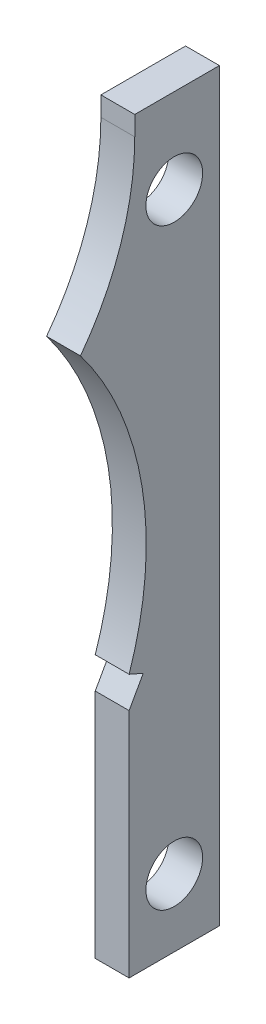
SolidWorks part; units mm, degrees
ref_plane "Front Plane" through (0, 0, 0) normal (0, 0, 1) x (1, 0, 0)
ref_plane "Top Plane" through (0, 0, 0) normal (0, 1, 0) x (1, 0, 0)
ref_plane "Right Plane" through (0, 0, 0) normal (1, 0, 0) x (0, 0, -1)
sketch "Sketch1" plane through (0, 0, 0) normal (1, 0, 0) x (0, 0, -1)
  line L0 (0, 55) -> (0, -55) construction
  line L1 (0, 66) -> (-15, 66)
  line L2 (0, 66) -> (0, -66)
  line L3 (0, -66) -> (-16, -66)
  line L4 (-15, 66) -> (-15, 62.56)
  line L5 (-16, -19.4031) -> (-13.5007, -20.5015)
  line L6 (-16, -24.97) -> (-16, -66)
  line L9 (-13.5007, -20.5015) -> (-16, -24.97)
  arc A1 (-16, -19.4031) -> (-24.621, 33.7655) centre (-70.52, -0.96) ccw
  arc A2 (-24.621, 33.7655) -> (-15, 62.56) centre (-62.9, 62.56) ccw
  point P7 (0, 0)
  dimension "D3" = 115.11
  dimension "D6" = 95.8
  dimension "D9" = 5.12
  dimension "D1" = 15
  dimension "D2" = 132
  dimension "D4" = 66.96
  dimension "D5" = 70.52
  dimension "D7" = 3.44
  dimension "D8" = 5.5669
  dimension "D10" = 41.03
  dimension "D11" = 16
  dimension "D13" = 2.73
extrude "Boss-Extrude1" add sketch "Sketch1" along normal mid plane 6
sketch "Sketch3" plane through (3, 0, 0) normal (1, 0, 0) x (0, 0, -1)
  line L0 (0, 66) -> (-15, 66) construction
  line L1 (0, 3.3) -> (0, -3.3) construction
  circle A0 centre (-8, 51) radius 5.025
  circle A1 centre (-8, -54) radius 5.025
  point P4 (0, 0)
  dimension "D1" = 10.05
  dimension "D2" = 15
  dimension "D3" = 8
  dimension "D4" = 105
extrude "Cut-Extrude1" cut sketch "Sketch3" against normal through all
